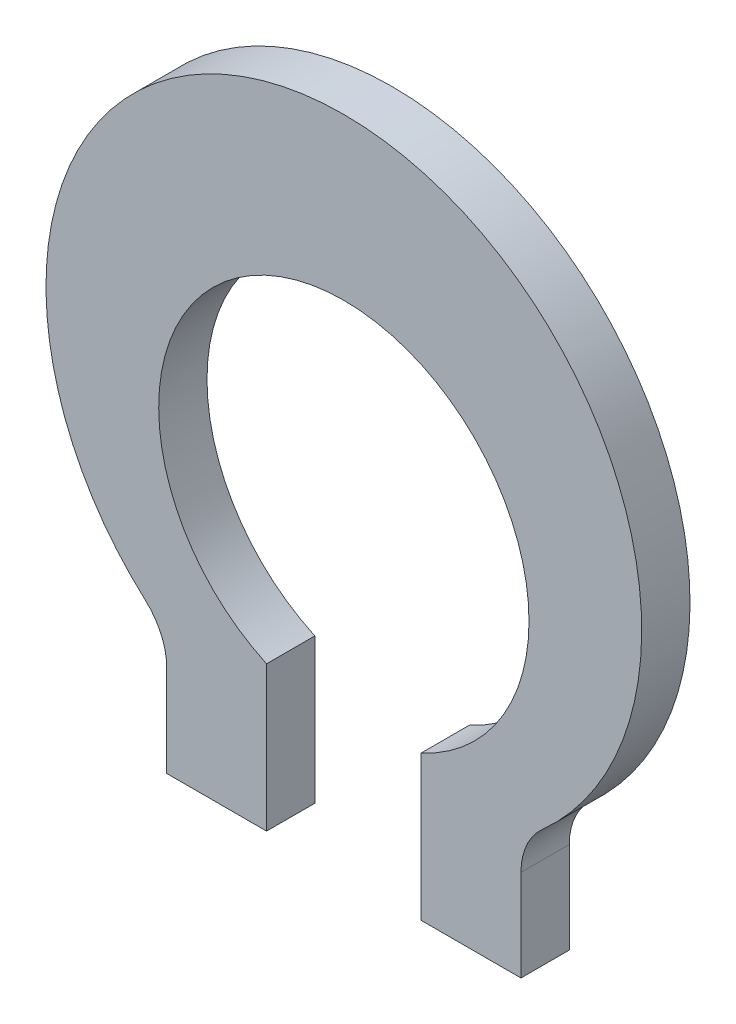
SolidWorks part; units mm, degrees
ref_plane "Front Plane" through (0, 0, 0) normal (0, 0, 1) x (1, 0, 0)
ref_plane "Top Plane" through (0, 0, 0) normal (0, 1, 0) x (1, 0, 0)
ref_plane "Right Plane" through (0, 0, 0) normal (1, 0, 0) x (0, 0, -1)
sketch "Sketch1" plane through (0, 0, 0) normal (0, 0, 1) x (1, 0, 0)
  line L0 (-2.4, 0) -> (-5.5, 0)
  line L1 (2.4, 0) -> (2.4, 4.5)
  line L2 (-2.4, 0) -> (-2.4, 4.5)
  line L3 (2.4, 0) -> (5.5, 0)
  line L4 (0, 0) -> (0, 21.8393) construction
  line L5 (-12.8987, 11.2252) -> (14.1054, 11.2252) construction
  line L6 (-5.5, 0) -> (-5.5, 3.7879)
  line L7 (5.5, 0) -> (5.5, 3.7879)
  line L8 (-12.8987, 9.7252) -> (14.1054, 9.7252) construction
  arc A0 (5.5, 3.7879) -> (-5.5, 3.7879) centre (0, 11.2252) ccw
  arc A1 (2.4, 4.5) -> (-2.4, 4.5) centre (0, 9.7252) ccw
  arc A2 (2.4, 4.5) -> (-2.4, 4.5) centre (0, 9.7252) ccw
  arc A3 (5.5, 3.7879) -> (-5.5, 3.7879) centre (0, 11.2252) ccw
  dimension "D1" = 11.5
  dimension "D2" = 18.5
  dimension "D3" = 1.5
  dimension "D4" = 3.1
  dimension "D5" = 4.5
  dimension "D6" = 4.8
extrude "Boss-Extrude1" add sketch "Sketch1" along normal blind 1.5 contours A1 L1 L3 L7 A0 L6 L0 L2
fillet "Fillet1" radius 2 2 edges at (-5.5, 3.7879, 0.75) (5.5, 3.7879, 0.75)
